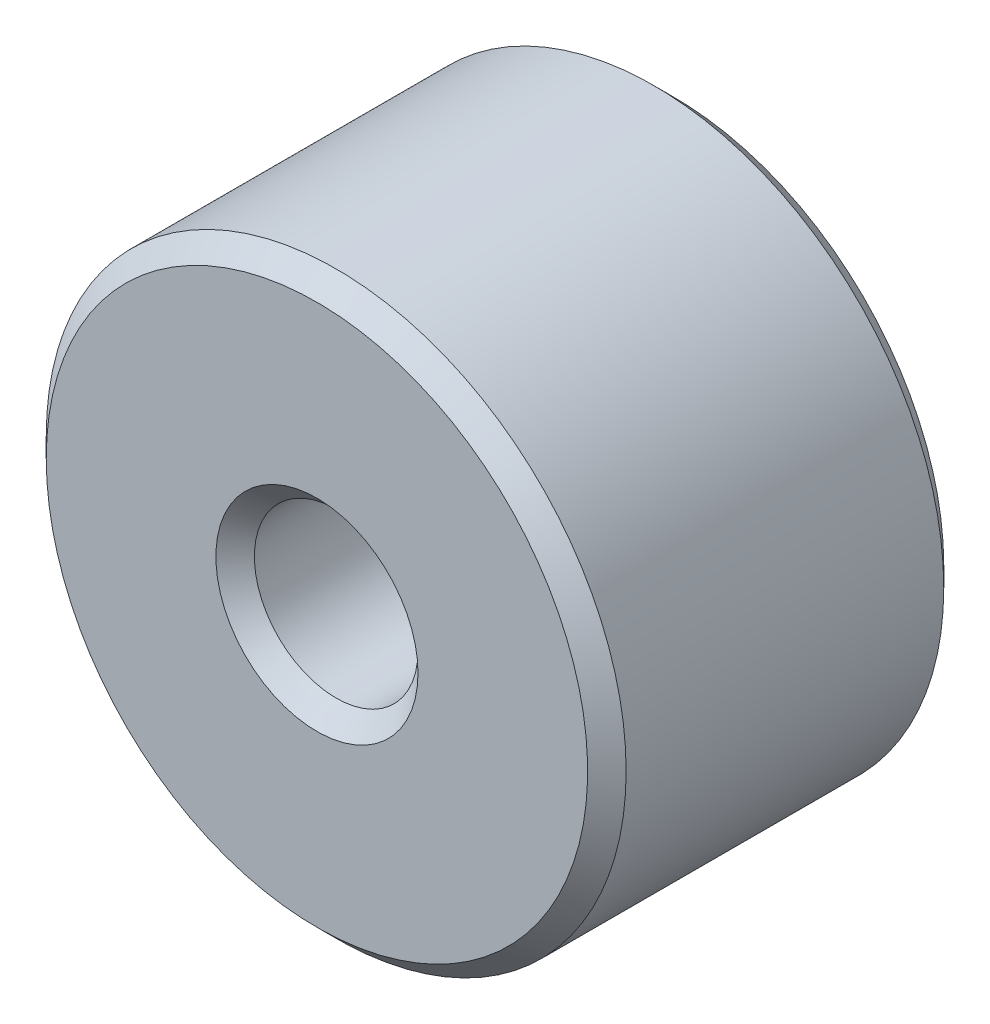
SolidWorks part; units mm, degrees
ref_plane "Front Plane" through (0, 0, 0) normal (0, 0, 1) x (1, 0, 0)
ref_plane "Top Plane" through (0, 0, 0) normal (0, 1, 0) x (1, 0, 0)
ref_plane "Right Plane" through (0, 0, 0) normal (1, 0, 0) x (0, 0, -1)
sketch "Sketch1" plane through (0, 0, 0) normal (0, 0, 1) x (1, 0, 0)
  circle A0 centre (0, 0) radius 6.025
  circle A1 centre (0, 0) radius 1.7
  dimension "D1" = 3.4
  dimension "D2" = 12.05
extrude "Boss-Extrude1" add sketch "Sketch1" along normal blind 7.4
chamfer "Chamfer1" distance 0.4 angle 45 4 edges at (1.7, 0, 0) (6.025, 0, 0) (6.025, 0, 7.4) (1.7, 0, 7.4)
